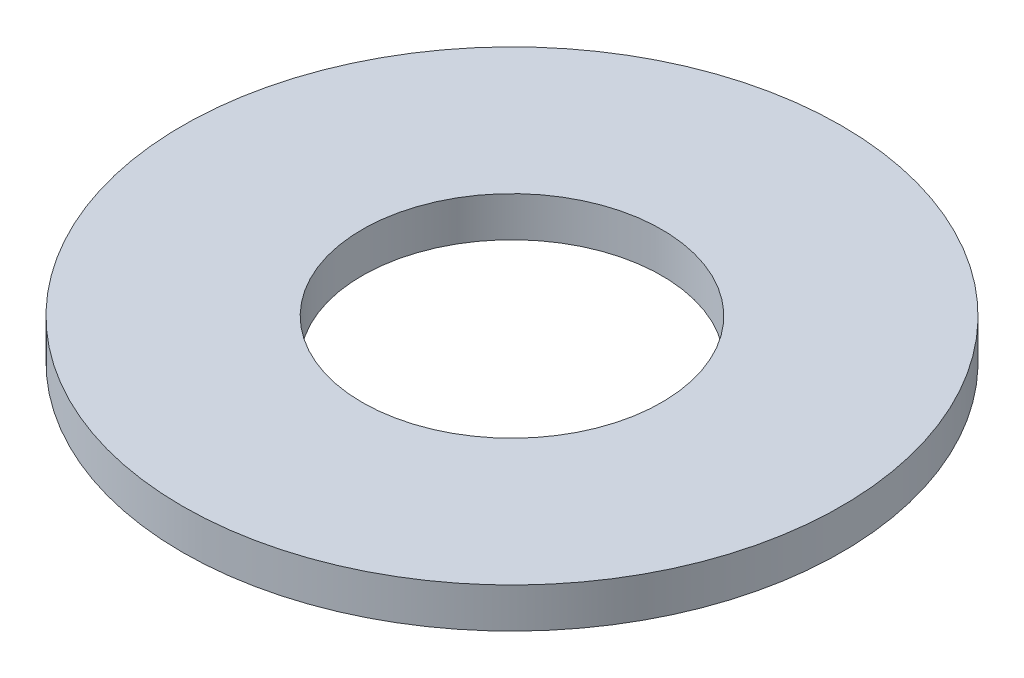
SolidWorks part; units mm, degrees
ref_plane "Front Plane" through (0, 0, 0) normal (0, 0, 1) x (1, 0, 0)
ref_plane "Top Plane" through (0, 0, 0) normal (0, 1, 0) x (1, 0, 0)
ref_plane "Right Plane" through (0, 0, 0) normal (1, 0, 0) x (0, 0, -1)
sketch "Sketch1" plane through (0, 0, 0) normal (0, 1, 0) x (1, 0, 0)
  line L0 (-156.7263, 0) -> (147.2044, 0) construction
  line L1 (0, -120.0539) -> (0, 109.5026) construction
  circle A0 centre (0, 0) radius 82.5
  circle A1 centre (0, 0) radius 37.5
  dimension "D1" = 165
  dimension "D2" = 75
extrude "Boss-Extrude1" add sketch "Sketch1" along normal blind 10
